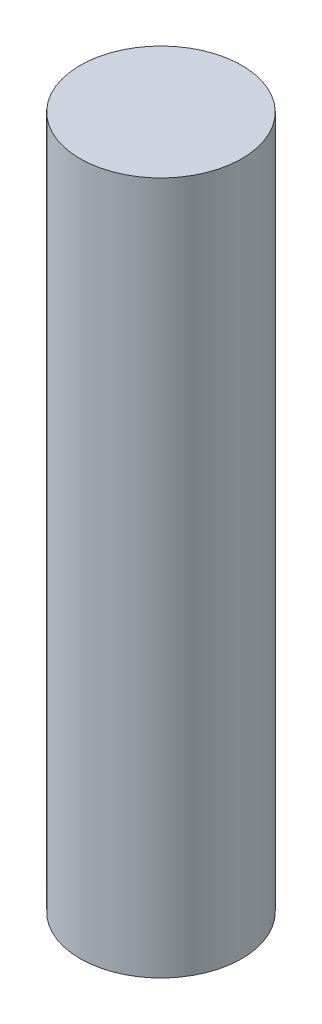
SolidWorks part; units mm, degrees
ref_plane "Front Plane" through (0, 0, 0) normal (0, 0, 1) x (1, 0, 0)
ref_plane "Top Plane" through (0, 0, 0) normal (0, 1, 0) x (1, 0, 0)
ref_plane "Right Plane" through (0, 0, 0) normal (1, 0, 0) x (0, 0, -1)
sketch "Sketch1" plane through (0, 0, 0) normal (0, 1, 0) x (1, 0, 0)
  circle A0 centre (0, 0) radius 1.75
  dimension "D1" = 3.5
extrude "Boss-Extrude1" add sketch "Sketch1" along normal blind 15
